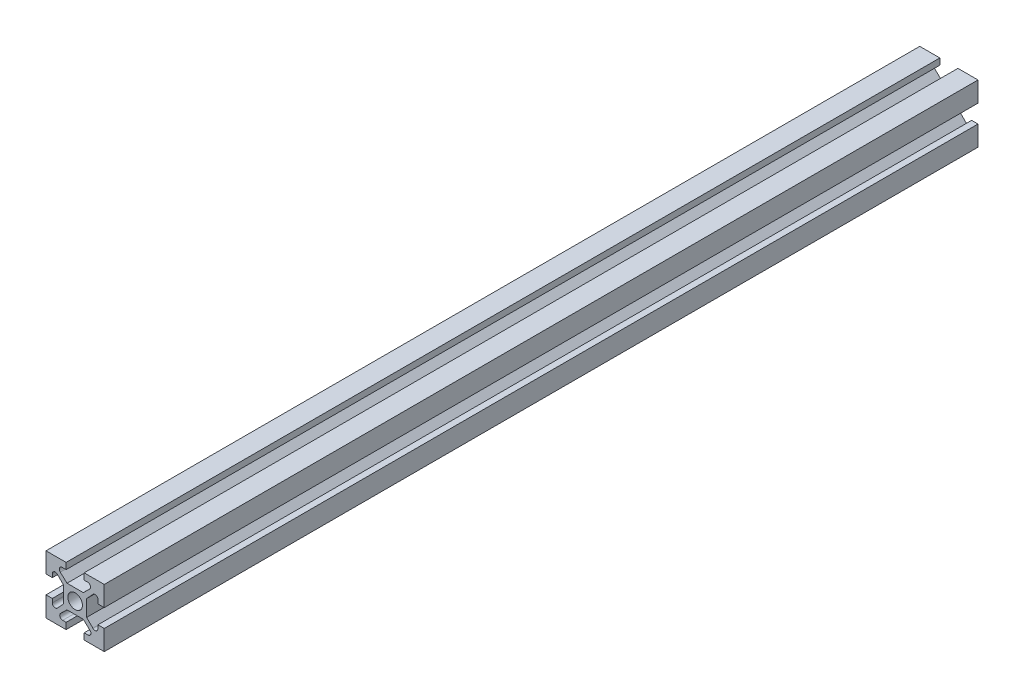
SolidWorks part; units mm, degrees
ref_plane "Front Plane" through (0, 0, 0) normal (0, 0, 1) x (1, 0, 0)
ref_plane "Top Plane" through (0, 0, 0) normal (0, 1, 0) x (1, 0, 0)
ref_plane "Right Plane" through (0, 0, 0) normal (1, 0, 0) x (0, 0, -1)
sketch "Sketch2" plane through (0, 0, 0) normal (0, 0, 1) x (1, 0, 0)
  line L0 (-295.6365, 99.3001) -> (355.6968, 99.3001) construction
  line L1 (53, 177) -> (305, 177) construction
  line L2 (0, 9.9554) -> (0, -10.0446) construction
  line L7 (-10, -10) -> (-3.1, -10)
  line L8 (-10, -10) -> (-10, -3.1)
  line L9 (-10, 10) -> (-3.1, 10)
  line L10 (10, -10) -> (10, -3.1)
  line L11 (-10, -10) -> (10, 10) construction
  line L12 (-10, 10) -> (10, -10) construction
  line L13 (-10, 0) -> (10, 0) construction
  line L14 (-10, 3.1) -> (-7.8186, 3.1)
  line L15 (-7.8186, 3.1) -> (-7.8186, 4.2854)
  line L16 (-6.1072, 4.9882) -> (-3.9647, 2.8197)
  line L17 (-3.9647, 2.8197) -> (-3.9647, 0)
  line L18 (-3.1, 10) -> (-3.1, 7.839)
  line L19 (-3.1, 7.839) -> (-4.4279, 7.839)
  line L20 (-5.1052, 6.1033) -> (-2.7827, 3.9647)
  line L21 (-2.7827, 3.9647) -> (0, 3.9647)
  line L22 (3.1, 10) -> (3.1, 7.8186)
  line L23 (3.1, 7.8186) -> (4.2854, 7.8186)
  line L24 (4.9882, 6.1072) -> (2.8197, 3.9647)
  line L25 (2.8197, 3.9647) -> (0, 3.9647)
  line L26 (6.1033, 5.1052) -> (3.9647, 2.7827)
  line L27 (3.9647, 2.7827) -> (3.9647, 0)
  line L28 (7.839, 3.1) -> (7.839, 4.4279)
  line L29 (10, 3.1) -> (7.839, 3.1)
  line L30 (10, -3.1) -> (7.8186, -3.1)
  line L31 (7.8186, -3.1) -> (7.8186, -4.2854)
  line L32 (6.1072, -4.9882) -> (3.9647, -2.8197)
  line L33 (3.9647, -2.8197) -> (3.9647, 0)
  line L34 (5.1052, -6.1033) -> (2.7827, -3.9647)
  line L35 (2.7827, -3.9647) -> (0, -3.9647)
  line L36 (3.1, -7.839) -> (4.4279, -7.839)
  line L37 (3.1, -10) -> (3.1, -7.839)
  line L38 (-3.1, -10) -> (-3.1, -7.8186)
  line L39 (-3.1, -7.8186) -> (-4.2854, -7.8186)
  line L40 (-4.9882, -6.1072) -> (-2.8197, -3.9647)
  line L41 (-2.8197, -3.9647) -> (0, -3.9647)
  line L42 (-6.1033, -5.1052) -> (-3.9647, -2.7827)
  line L43 (-3.9647, -2.7827) -> (-3.9647, 0)
  line L44 (-7.839, -3.1) -> (-7.839, -4.4279)
  line L45 (-10, -3.1) -> (-7.839, -3.1)
  line L46 (3.1, 10) -> (10, 10)
  line L47 (10, 3.1) -> (10, 10)
  line L48 (3.1, -10) -> (10, -10)
  line L49 (-10, 3.1) -> (-10, 10)
  circle A1 centre (0, 0) radius 2.5
  arc A2 (-4.4279, 7.839) -> (-5.1052, 6.1033) centre (-4.4279, 6.839) ccw
  arc A3 (-7.8186, 4.2854) -> (-6.1072, 4.9882) centre (-6.8186, 4.2854) cw
  arc A4 (4.2854, 7.8186) -> (4.9882, 6.1072) centre (4.2854, 6.8186) cw
  arc A5 (7.839, 4.4279) -> (6.1033, 5.1052) centre (6.839, 4.4279) ccw
  arc A6 (7.8186, -4.2854) -> (6.1072, -4.9882) centre (6.8186, -4.2854) cw
  arc A7 (4.4279, -7.839) -> (5.1052, -6.1033) centre (4.4279, -6.839) ccw
  arc A8 (-4.2854, -7.8186) -> (-4.9882, -6.1072) centre (-4.2854, -6.8186) cw
  arc A9 (-7.839, -4.4279) -> (-6.1033, -5.1052) centre (-6.839, -4.4279) ccw
  dimension "D1" = 3.1
  dimension "D5" = 1
  dimension "D2" = 20
  dimension "D3" = 20
  dimension "D4" = 3.1
  dimension "D6" = 4
extrude "Boss-Extrude1" add sketch "Sketch2" along normal blind 300
